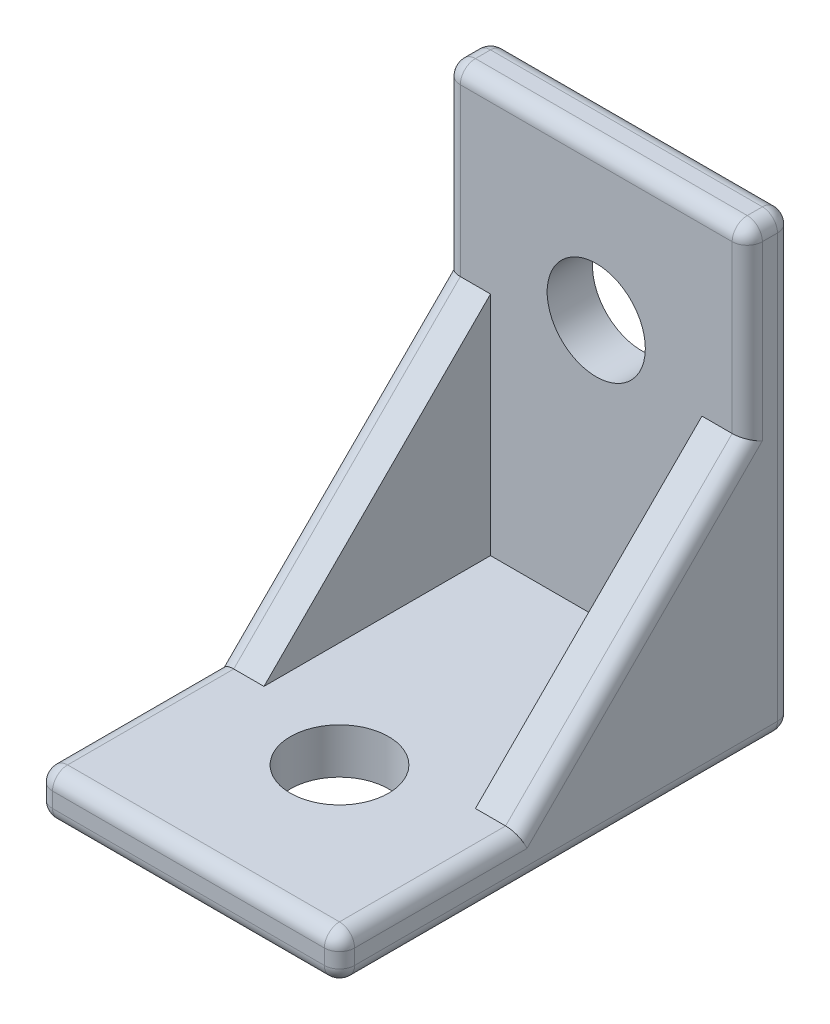
SolidWorks part; units mm, degrees
ref_plane "Front Plane" through (0, 0, 0) normal (0, 0, 1) x (1, 0, 0)
ref_plane "Top Plane" through (0, 0, 0) normal (0, 1, 0) x (1, 0, 0)
ref_plane "Right Plane" through (0, 0, 0) normal (1, 0, 0) x (0, 0, -1)
sketch "Sketch1" plane through (0, 0, 0) normal (0, 1, 0) x (1, 0, 0)
  line L1 (0, 0) -> (-20, 0)
  line L2 (0, 0) -> (0, 30)
  line L3 (0, 30) -> (-20, 30)
  line L4 (-20, 0) -> (-20, 30)
  circle A0 centre (-10, 10) radius 3.25
  point P7 (0, 0)
  point P8 (-10, 30)
  dimension "D3" = 6.5
  dimension "D1" = 20
  dimension "D2" = 30
  dimension "D4" = 20
extrude "Boss-Extrude1" add sketch "Sketch1" along normal blind 3
sketch "Sketch2" plane through (0, 3, 0) normal (0, 1, 0) x (1, 0, 0)
  line L0 (0, 0) -> (0, 30) construction
  line L1 (-20, 30) -> (0, 30)
  line L2 (-20, 30) -> (-20, 27)
  line L3 (-20, 27) -> (0, 27)
  line L4 (0, 30) -> (0, 27)
  dimension "D1" = 3
extrude "Boss-Extrude2" add sketch "Sketch2" along normal blind 27
sketch "Sketch3" plane through (0, 0, -27) normal (0, 0, 1) x (1, 0, 0)
  line L0 (-20, 0) -> (0, 0) construction
  line L1 (-20, 30) -> (0, 30) construction
  circle A0 centre (-10, 20) radius 3.25
  point P4 (0, 0)
  point P7 (-10, 30)
  dimension "D1" = 6.5
  dimension "D2" = 20
extrude "Cut-Extrude1" cut sketch "Sketch3" against normal through all
sketch "Sketch5" plane through (0, 0, 0) normal (1, 0, 0) x (0, 0, -1)
  line L0 (12, 3) -> (27, 18)
  line L1 (0, 3) -> (27, 3) construction
  line L2 (27, 18) -> (27, 3)
  line L3 (27, 3) -> (12, 3)
  dimension "D1" = 15
  dimension "D2" = 15
extrude "Boss-Extrude3" add sketch "Sketch5" against normal blind 3
ref_plane "Plane1" through (-10, 0, 0) normal (-1, 0, 0) x (0, 0, 1)
mirror "Mirror1" about plane through (-10, 0, 0) normal (-1, 0, 0) of "Boss-Extrude3"
fillet "Fillet1" radius 1 19 edges at (-10, 30, -30) (-10, 30, -27) (-10, 3, 0) (-10, 0, 0) (-20, 1.5, 0) (-20, 0, -15) (-20, 15, -30) (-20, 30, -28.5) (-20, 24, -27) (-20, 10.5, -19.5) (-20, 3, -6) (0, 1.5, 0) (0, 3, -6) (0, 10.5, -19.5) (0, 24, -27) (0, 30, -28.5) (0, 15, -30) (0, 0, -15) (-10, 0, -30)
